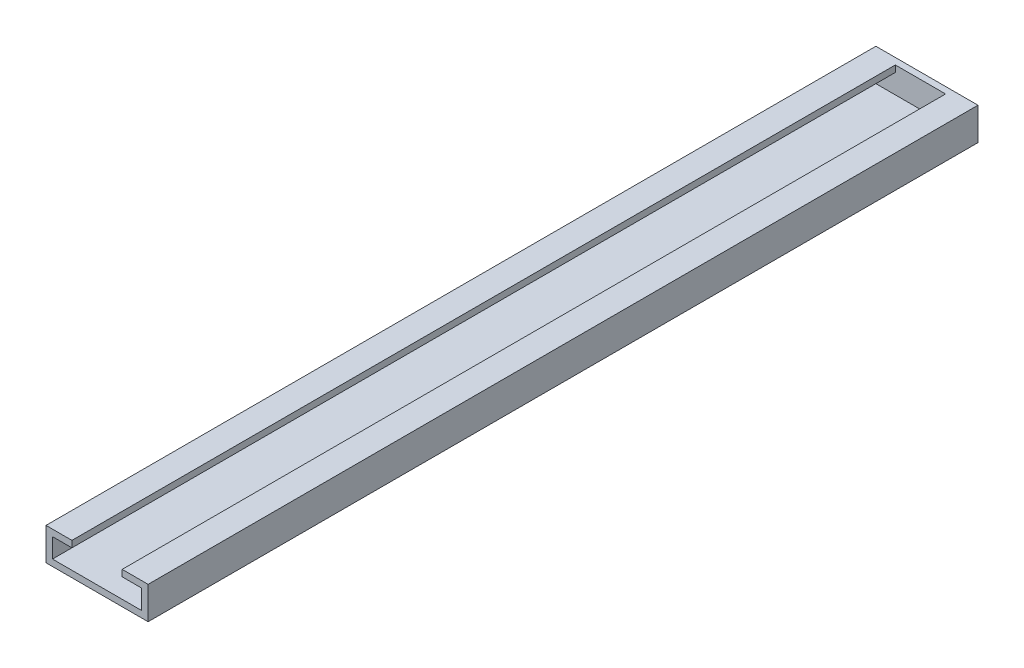
SolidWorks part; units mm, degrees
ref_plane "Front Plane" through (0, 0, 0) normal (0, 0, 1) x (1, 0, 0)
ref_plane "Top Plane" through (0, 0, 0) normal (0, 1, 0) x (1, 0, 0)
ref_plane "Right Plane" through (0, 0, 0) normal (1, 0, 0) x (0, 0, -1)
sketch "Sketch1" plane through (0, 0, 0) normal (0, 0, 1) x (1, 0, 0)
  line L1 (3.1, 1.4073) -> (3.1, 0.6073)
  line L2 (3.1, 0.6073) -> (5.5, 0.6073)
  line L3 (5.5, 0.6073) -> (5.5, -1.7927)
  line L4 (5.5, -1.7927) -> (-5.5, -1.7927)
  line L5 (0, -55) -> (0, 55) construction
  line L6 (-5.5, 0.6073) -> (-5.5, -1.7927)
  line L7 (-3.1, 0.6073) -> (-5.5, 0.6073)
  line L8 (-3.1, 1.4073) -> (-3.1, 0.6073)
  line L9 (3.1, 1.4073) -> (6.3, 1.4073)
  line L10 (-6.3, -2.5927) -> (6.3, -2.5927)
  line L11 (-6.3, -2.5927) -> (-6.3, 1.4073)
  line L12 (-6.3, 1.4073) -> (-3.1, 1.4073)
  line L13 (6.3, -2.5927) -> (6.3, 1.4073)
  point P10 (0, -1.7927)
  point P13 (0, 0)
  point P17 (-6.3, -0.5927)
  dimension "D1" = 3.1
  dimension "D2" = 0.8
  dimension "D3" = 0.8
  dimension "D4" = 0.8
  dimension "D5" = 0.8
  dimension "D6" = 2.4
  dimension "D7" = 2.4
extrude "Boss-Extrude1" add sketch "Sketch1" along normal blind 101.6 contours L8 L7 L6 L4 L3 L2 L1 L9 L13 L10 L11 L12
sketch "Sketch2" plane through (-6.3, 0, 0) normal (-1, 0, 0) x (0, 0, 1)
  line L0 (101.6, 1.4073) -> (0, 1.4073) construction
  line L1 (0, -2.5927) -> (-0.8, -2.5927)
  line L2 (0, -2.5927) -> (0, 1.4073)
  line L3 (0, 1.4073) -> (-0.8, 1.4073)
  line L4 (-0.8, -2.5927) -> (-0.8, 1.4073)
  dimension "D1" = 0.8
extrude "Boss-Extrude2" add sketch "Sketch2" against normal up to surface (12.6 mm away) up to face at (6.3, -0.5927, 50.8)
